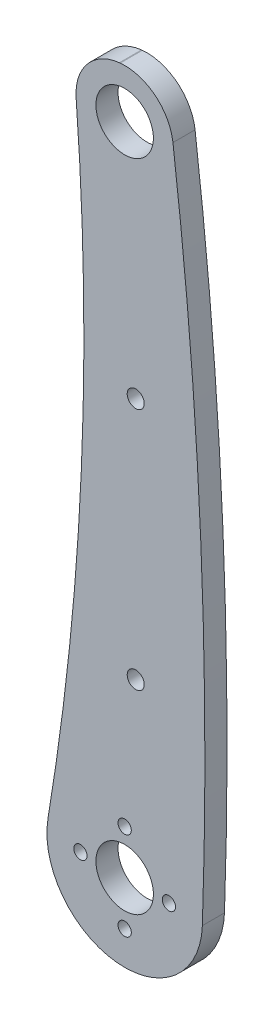
SolidWorks part; units mm, degrees
ref_plane "前视基准面" through (0, 0, 0) normal (0, 0, 1) x (1, 0, 0)
ref_plane "上视基准面" through (0, 0, 0) normal (0, 1, 0) x (1, 0, 0)
ref_plane "右视基准面" through (0, 0, 0) normal (1, 0, 0) x (0, 0, -1)
sketch "草图1" plane through (0, 0, 0) normal (0, 0, 1) x (1, 0, 0)
  line B0 (-1.1971, 158.9347) -> (-0.9981, 158.9546)
  line B1 (-1.8501, -17.4774) -> (-1.6511, -17.4973)
  circle B2 centre (2.5, 40) radius 1.925
  circle B3 centre (2.5, 95) radius 1.925
  arc B4 (-1.1971, 158.9347) -> (-10.9678, 147.1591) centre (0, 148) ccw
  arc B5 (10.9164, 149.3539) -> (-0.9981, 158.9546) centre (0, 148) ccw
  arc B6 (-17.337, 2.8825) -> (-10.9678, 147.1591) centre (-609.2119, 101.2901) ccw
  arc B7 (-1.6511, -17.4973) -> (17.5644, -0.6113) centre (0, 0) ccw
  arc B8 (-17.337, 2.8825) -> (-1.8501, -17.4774) centre (0, 0) ccw
  arc B9 (17.5644, -0.6113) -> (10.9164, 149.3539) centre (-931.8609, 32.4303) ccw
  circle B10 centre (10, 0) radius 0.925
  circle B11 centre (0, -10) radius 0.925
  circle B12 centre (0, 10) radius 0.925
  circle B13 centre (-10, 0) radius 0.925
  circle B14 centre (0, 0) radius 6.5
  circle B15 centre (0, 148) radius 6.5
sketch_block_instance "块1-1"
sketch_block "块1"
extrude "凸台-拉伸1" add sketch "草图1" along normal blind 5
sketch "草图2" plane through (0, 0, 5) normal (0, 0, 1) x (1, 0, 0)
  circle A0 centre (0, 10) radius 1.5
  circle A1 centre (10, 0) radius 1.5
  circle A2 centre (-10, 0) radius 1.5
  circle A3 centre (0, -10) radius 1.5
  dimension "D1" = 3
extrude "切除-拉伸1" cut sketch "草图2" against normal through all
